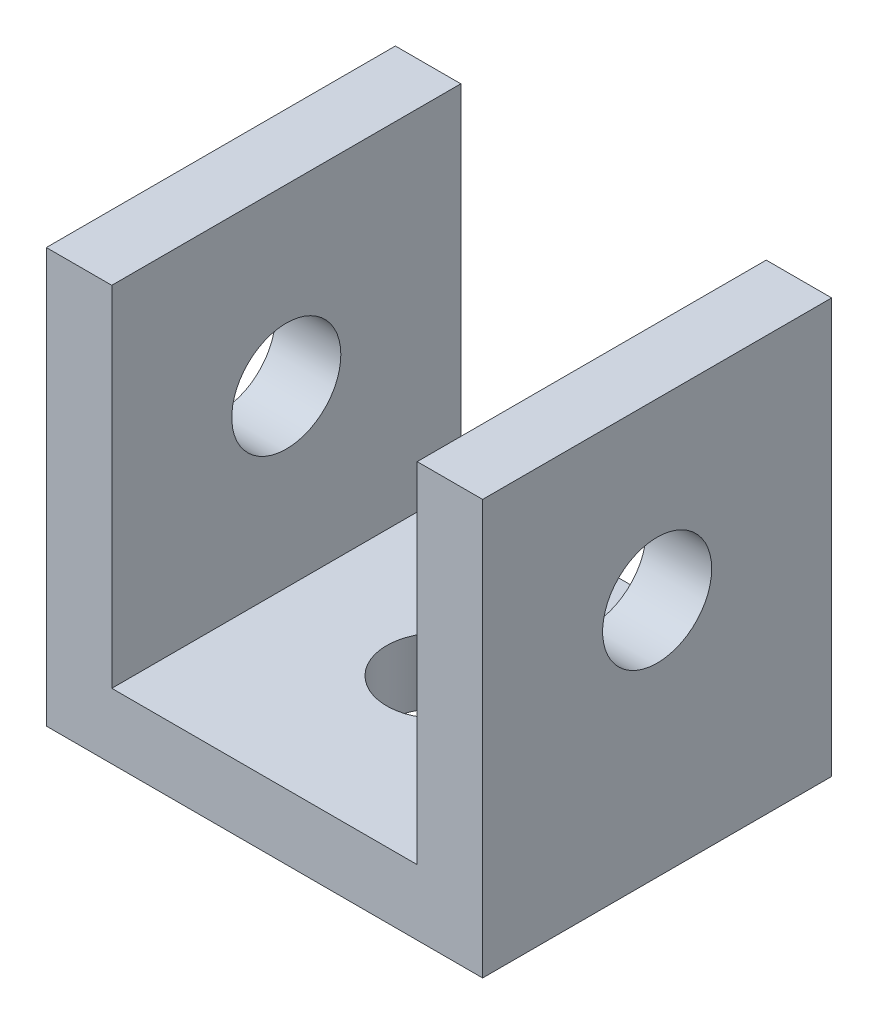
SolidWorks part; units mm, degrees
ref_plane "Front Plane" through (0, 0, 0) normal (0, 0, 1) x (1, 0, 0)
ref_plane "Top Plane" through (0, 0, 0) normal (0, 1, 0) x (1, 0, 0)
ref_plane "Right Plane" through (0, 0, 0) normal (1, 0, 0) x (0, 0, -1)
sketch "Sketch1" plane through (0, 0, 0) normal (0, 1, 0) x (1, 0, 0)
  line L1 (-5, -4) -> (5, -4)
  line L2 (-5, -4) -> (-5, 4)
  line L3 (-5, 4) -> (5, 4)
  line L4 (5, -4) -> (5, 4)
  line L5 (-5, -4) -> (5, 4) construction
  line L6 (-5, 4) -> (5, -4) construction
  point P0 (0, 0)
  dimension "D1" = 10
  dimension "D2" = 8
extrude "Boss-Extrude1" add sketch "Sketch1" along normal blind 1.5
sketch "Sketch2" plane through (0, 1.5, 0) normal (0, 1, 0) x (1, 0, 0)
  line L0 (-5, -4) -> (5, -4) construction
  line L1 (-5, 4) -> (-3.5, 4)
  line L2 (-5, 4) -> (-5, -4)
  line L3 (-5, -4) -> (-3.5, -4)
  line L4 (-3.5, 4) -> (-3.5, -4)
  dimension "D1" = 1.5
extrude "Boss-Extrude2" add sketch "Sketch2" along normal blind 8
sketch "Sketch4" plane through (-3.5, 0, 0) normal (1, 0, 0) x (0, 0, -1)
  line L0 (-4, 5.5) -> (4, 5.5) construction
  line L1 (-4, 9.5) -> (-4, 1.5) construction
  line L2 (4, 9.5) -> (4, 1.5) construction
  line L4 (-4, 1.5) -> (4, 1.5) construction
  line L5 (0, 1.5) -> (0, 9.5) construction
  line L6 (-4, 9.5) -> (4, 9.5) construction
  circle A1 centre (0, 5.5) radius 1.25
  dimension "D1" = 2.5
extrude "Cut-Extrude1" cut sketch "Sketch4" against normal through all
mirror "Mirror2" about plane through (0, 0, 0) normal (1, 0, 0) of "Cut-Extrude1", "Boss-Extrude2"
sketch "Sketch5" plane through (0, 0, 0) normal (0, 1, 0) x (1, 0, 0)
  circle A0 centre (0, 0) radius 1.2
  dimension "D1" = 2.4
extrude "Cut-Extrude2" cut sketch "Sketch5" along normal through all
